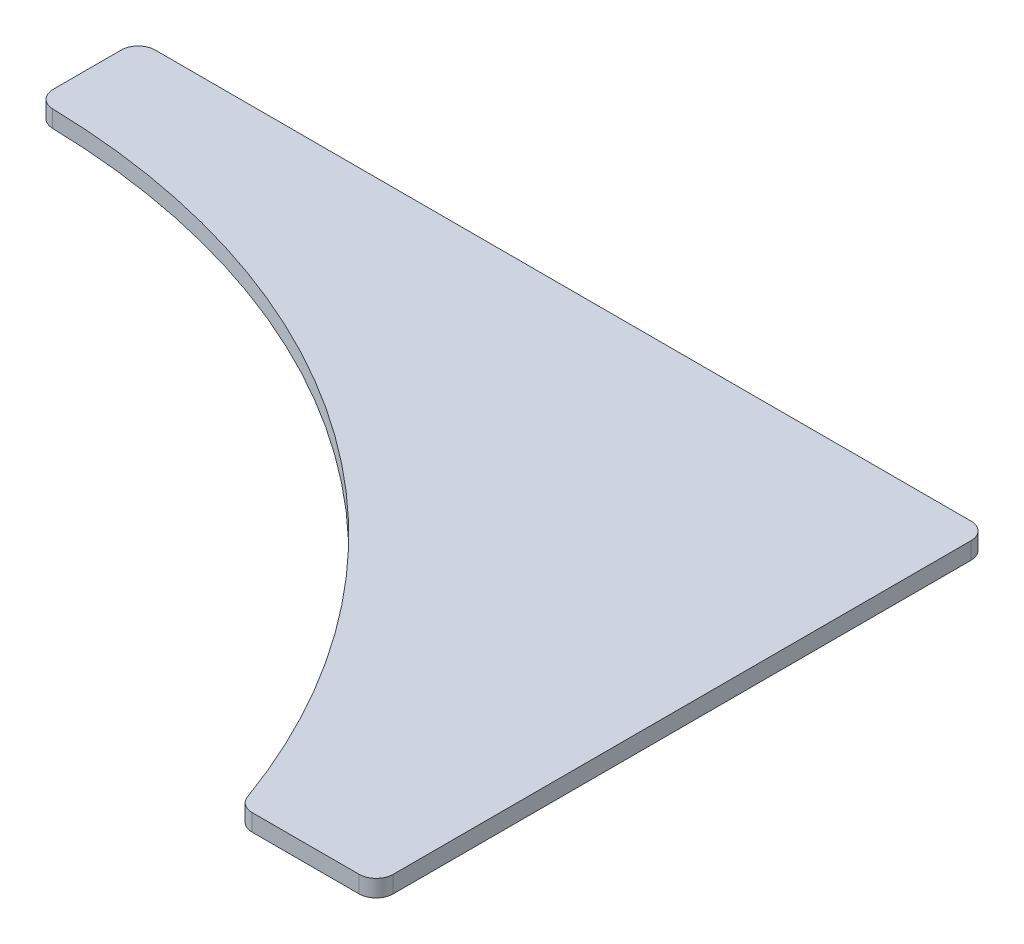
SolidWorks part; units mm, degrees
ref_plane "Front Plane" through (0, 0, 0) normal (0, 0, 1) x (1, 0, 0)
ref_plane "Top Plane" through (0, 0, 0) normal (0, 1, 0) x (1, 0, 0)
ref_plane "Right Plane" through (0, 0, 0) normal (1, 0, 0) x (0, 0, -1)
sketch "Sketch1" plane through (0, 0, 0) normal (0, 1, 0) x (1, 0, 0)
  line L0 (0, 0) -> (0, 228.6)
  line L1 (0, 228.6) -> (-317.5, 228.6)
  line L2 (-317.5, 228.6) -> (-317.5, 190.5)
  line L3 (-50.8, 0) -> (0, 0)
  line L4 (-317.5, 190.5) -> (-414.3826, 190.5) construction
  arc A0 (-317.5, 190.5) -> (-50.8, 0) centre (-317.5, -91.44) cw
  dimension "D3" = 50.8
  dimension "D1" = 228.6
  dimension "D2" = 317.5
  dimension "D4" = 38.1
extrude "Boss-Extrude1" add sketch "Sketch1" along normal blind 6.35
fillet "Fillet1" radius 6.35 5 edges at (-317.5, 3.175, -190.5) (-317.5, 3.175, -228.6) (0, 3.175, -228.6) (-50.8, 3.175, 0) (0, 3.175, 0)
